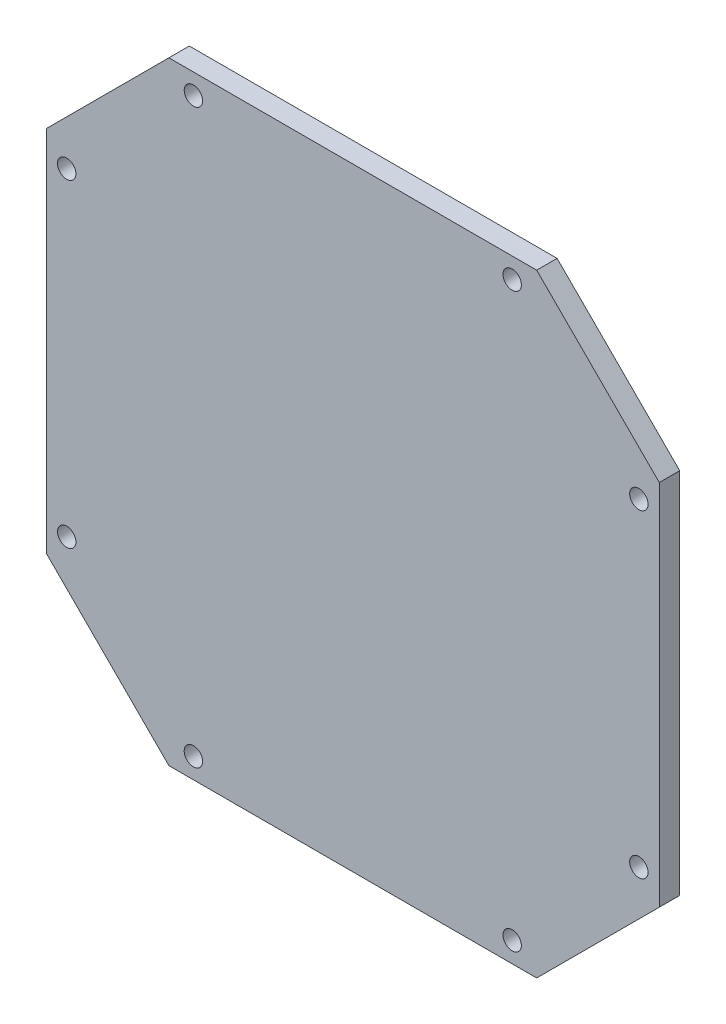
SolidWorks part; units mm, degrees
ref_plane "Front Plane" through (0, 0, 0) normal (0, 0, 1) x (1, 0, 0)
ref_plane "Top Plane" through (0, 0, 0) normal (0, 1, 0) x (1, 0, 0)
ref_plane "Right Plane" through (0, 0, 0) normal (1, 0, 0) x (0, 0, -1)
sketch "Sketch1" plane through (0, 0, 0) normal (0, 0, 1) x (1, 0, 0)
  line L4 (60, 0) -> (0, 60)
  line L5 (60, 0) -> (240, 0)
  line L6 (0, 60) -> (0, 240)
  line L7 (60, 300) -> (240, 300)
  line L8 (300, 60) -> (300, 240)
  line L9 (240, 0) -> (300, 60)
  line L10 (240, 300) -> (300, 240)
  line L11 (0, 240) -> (60, 300)
  point P0 (0, 0)
  point P1 (300, 300)
  point P3 (0, 300)
  point P4 (300, 0)
  dimension "D1" = 300
  dimension "D2" = 60
  dimension "D3" = 45
  dimension "D4" = 60
  dimension "D5" = 45
  dimension "D6" = 60
  dimension "D7" = 45
  dimension "D8" = 60
  dimension "D9" = 45
extrude "Boss-Extrude1" add sketch "Sketch1" along normal blind 10
hole_wizard "Ø1.0mm Dowel Hole1" positions "Sketch3" profile "Sketch5" hole size "Ø1.0" standard "ISO" end condition through all
sketch "Sketch3" plane through (0, 0, 10) normal (0, 0, 1) x (1, 0, 0)
  line L0 (0, 240) -> (0, 60) construction
  line L1 (300, 60) -> (300, 240) construction
  line L2 (240, 300) -> (60, 300) construction
  point P0 (10, 228)
  point P2 (290, 228)
  point P4 (228, 290)
  point P6 (72, 290)
  dimension "D1" = 62
  dimension "D2" = 62
  dimension "D3" = 156
  dimension "D4" = 62
  dimension "D5" = 10
  dimension "D6" = 10
  dimension "D7" = 10
  dimension "D8" = 62
sketch "Sketch5" plane through (10, 228, 10) normal (1, 0, 0) x (0, -1, 0)
  line L0 (0, 0) -> (0, 10)
  line L1 (0, 10) -> (4.5, 10)
  line L2 (4.5, 10) -> (4.5, 0)
  line L5 (4.5, 0) -> (0, 0)
  line L11 (0, -6.35) -> (0, 107.95) construction
  dimension "Thru Hole Dia." = 9
  dimension "Thru Hole Depth" = 10
sketch "Sketch6" plane through (0, 0, 10) normal (0, 0, 1) x (1, 0, 0)
  line L0 (0, 150) -> (300, 150) construction
  line L1 (0, 240) -> (0, 60) construction
  line L2 (300, 60) -> (300, 240) construction
ref_plane "Plane1" through (0, 150, 0) normal (0, -1, 0) x (-1, 0, 0)
mirror "Mirror1" about plane through (0, 150, 0) normal (0, -1, 0) of "Ø1.0mm Dowel Hole1"
